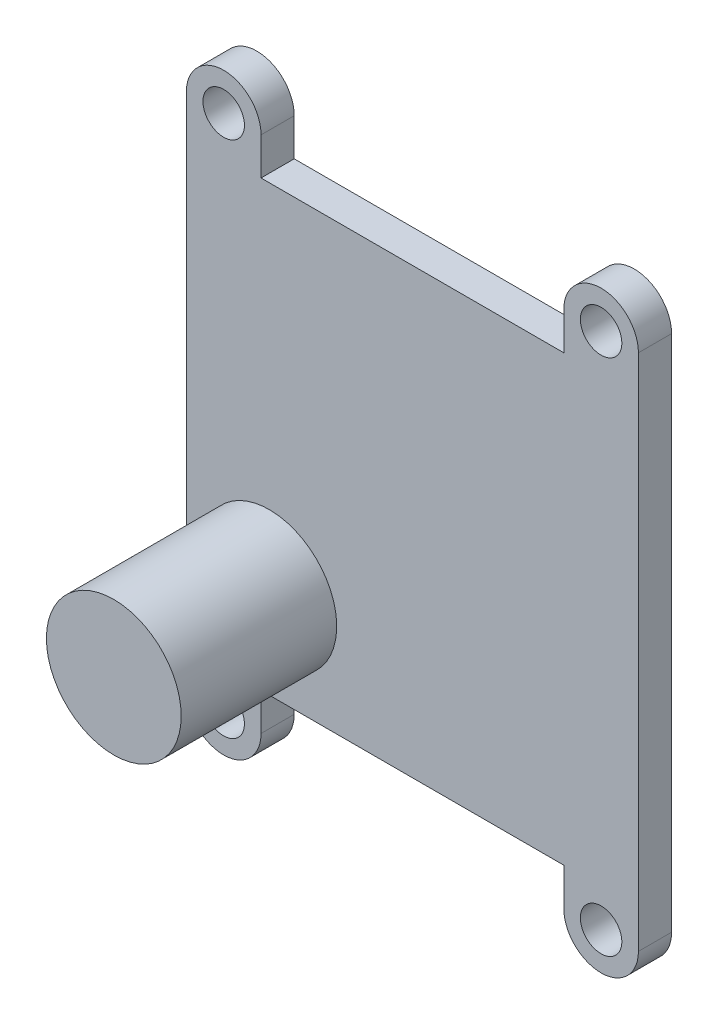
SolidWorks part; units mm, degrees
ref_plane "Front Plane" through (0, 0, 0) normal (0, 0, 1) x (1, 0, 0)
ref_plane "Top Plane" through (0, 0, 0) normal (0, 1, 0) x (1, 0, 0)
ref_plane "Right Plane" through (0, 0, 0) normal (1, 0, 0) x (0, 0, -1)
sketch "Sketch1" plane through (0, 0, 0) normal (0, 0, 1) x (1, 0, 0)
  line L0 (0, 10.7) -> (0, -10.7) construction
  line L2 (-10.9, 10.7) -> (-10.9, -10.7)
  line L3 (-7.3, -10.7) -> (7.3, -10.7)
  line L4 (10.9, 10.7) -> (10.9, -10.7)
  line L6 (-10.9, 0) -> (10.9, 0) construction
  line L7 (-10.9, 12.5) -> (-10.9, 10.7)
  line L9 (-7.3, 12.5) -> (-7.3, 10.7)
  line L10 (-7.3, 10.7) -> (7.3, 10.7)
  line L11 (10.9, 12.5) -> (10.9, 10.7)
  line L12 (7.3, 12.5) -> (7.3, 10.7)
  line L13 (10.9, -12.5) -> (10.9, -10.7)
  line L14 (7.3, -12.5) -> (7.3, -10.7)
  line L15 (-10.9, -12.5) -> (-10.9, -10.7)
  line L16 (-7.3, -12.5) -> (-7.3, -10.7)
  circle A1 centre (-9.1, 12.5) radius 1
  arc A2 (-7.3, 12.5) -> (-10.9, 12.5) centre (-9.1, 12.5) ccw
  circle A3 centre (9.1, 12.5) radius 1
  arc A4 (7.3, 12.5) -> (10.9, 12.5) centre (9.1, 12.5) cw
  arc A5 (7.3, -12.5) -> (10.9, -12.5) centre (9.1, -12.5) ccw
  circle A6 centre (9.1, -12.5) radius 1
  circle A7 centre (-9.1, -12.5) radius 1
  arc A8 (-7.3, -12.5) -> (-10.9, -12.5) centre (-9.1, -12.5) cw
  point P6 (-10.9, 0)
  point P21 (0, 0)
  dimension "D3" = 3.6
  dimension "D4" = 2
  dimension "D1" = 21.8
  dimension "D2" = 21.4
extrude "Boss-Extrude1" add sketch "Sketch1" along normal blind 1.6
sketch "Sketch2" plane through (0, 0, 1.6) normal (0, 0, 1) x (1, 0, 0)
  line L0 (-7.3, -10.7) -> (7.3, -10.7) construction
  line L1 (-10.9, 12.5) -> (-10.9, -12.5) construction
  circle A0 centre (-6.9, -6.2) radius 3.25
  dimension "D3" = 6.5
  dimension "D1" = 4.5
  dimension "D2" = 4
extrude "Boss-Extrude2" add sketch "Sketch2" along normal blind 7.5
